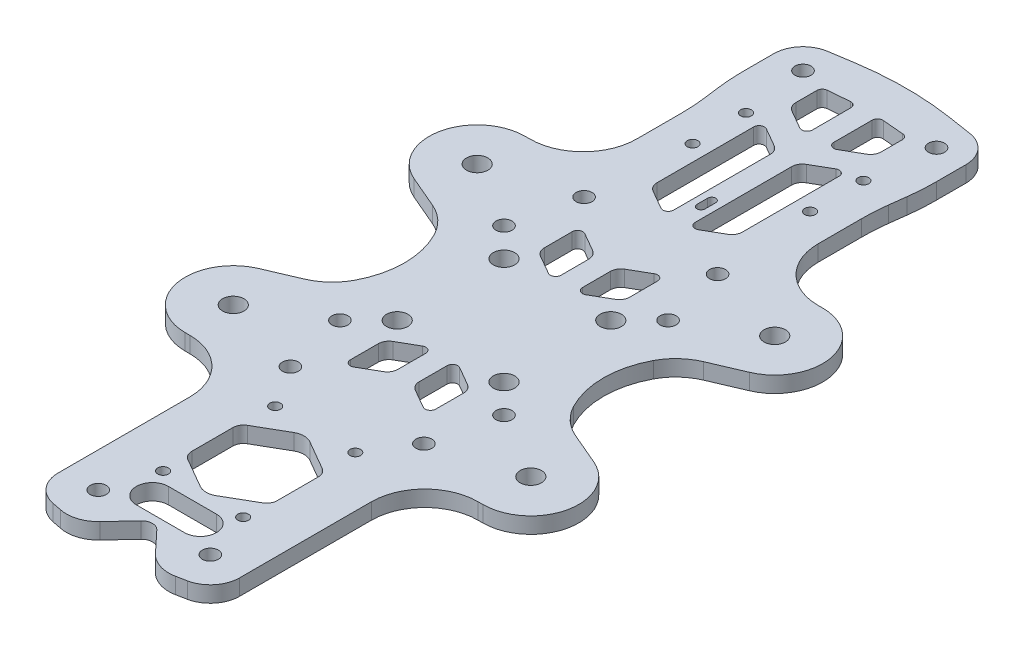
SolidWorks part; units mm, degrees
other "Markup1"
sketch "Sketch3" plane through (-36.8644, 3, -75.3176) normal (0, 1, 0) x (1, 0, 0)
material "Thornel Mat VMA"
ref_plane "Front Plane" through (0, 0, 0) normal (0, 0, 1) x (1, 0, 0)
ref_plane "Top Plane" through (0, 0, 0) normal (0, 1, 0) x (1, 0, 0)
ref_plane "Right Plane" through (0, 0, 0) normal (1, 0, 0) x (0, 0, -1)
sketch "Sketch1" plane through (0, 0, 0) normal (0, 1, 0) x (1, 0, 0)
  line L0 (7.0144, -13.8425) -> (3.5179, -11.8157)
  line L1 (-1.9927, -17.8721) -> (-1.9837, -12.6721)
  line L2 (-6.9856, 13.8181) -> (-3.4821, 11.8035)
  line L3 (2.0122, 17.9008) -> (2.0164, 12.6801)
  line L4 (2, 51.8812) -> (2, 33.7679)
  line L5 (-7, 34.9226) -> (-3.5, 32.9019)
  line L6 (3.5, 58.9019) -> (7, 60.9226)
  line L7 (-7, 60.9226) -> (-3.5, 58.9019)
  line L8 (-1.5, -37.866) -> (-7, -41.0415)
  line L9 (-6.6638, -69.1081) -> (-2.9181, -65.1127)
  line L10 (2.0164, -12.6801) -> (2.0122, -17.9008)
  line L11 (3, -19.6132) -> (6.5, -21.634)
  line L12 (8.002, -20.7686) -> (8.0113, -15.5764)
  line L13 (-3.4821, -11.8035) -> (-6.9856, -13.8181)
  line L14 (-7.9886, -15.5483) -> (-7.9977, -20.7675)
  line L15 (-6.5, -21.634) -> (-3, -19.6133)
  line L16 (-1.9837, 12.6721) -> (-1.9927, 17.8721)
  line L17 (-3, 19.6133) -> (-6.5, 21.634)
  line L18 (-7.9977, 20.7675) -> (-7.9886, 15.5483)
  line L19 (3.5179, 11.8157) -> (7.0144, 13.8425)
  line L20 (8.0113, 15.5764) -> (8.002, 20.7686)
  line L21 (6.5, 21.634) -> (3, 19.6132)
  line L22 (3.5, 32.9019) -> (7, 34.9226)
  line L23 (8, 36.6547) -> (8, 54.7679)
  line L24 (6.5, 55.634) -> (3, 53.6132)
  line L25 (-2, 33.7679) -> (-2, 51.8812)
  line L26 (-3, 53.6133) -> (-6.5, 55.634)
  line L27 (-8, 54.7679) -> (-8, 36.6546)
  line L28 (8, 62.6547) -> (8, 66.5946)
  line L29 (7.0872, 67.5908) -> (3.0872, 67.9408)
  line L30 (2, 66.9446) -> (2, 59.7679)
  line L31 (-2, 59.7679) -> (-2, 66.9446)
  line L32 (-3.0872, 67.9408) -> (-7.0872, 67.5908)
  line L33 (-8, 66.5946) -> (-8, 62.6547)
  line L34 (-8, -42.7735) -> (-8, -50.4641)
  line L35 (-7, -52.1962) -> (-1.5, -55.3716)
  line L36 (1.5, -55.3716) -> (7, -52.1962)
  line L37 (8, -50.4641) -> (8, -42.7735)
  line L38 (7, -41.0415) -> (1.5, -37.866)
  line L39 (-12.1839, -69.9325) -> (-10.3636, -70.2952)
  line L40 (-15, -41.84) -> (-15, -66.5)
  line L41 (-27.8644, -29.84) -> (-27, -29.84)
  line L42 (-24.6147, -13.8367) -> (-30.6171, -16.404)
  line L43 (-30.6171, 16.404) -> (-24.6147, 13.8367)
  line L44 (-26.9944, 29.84) -> (-27.8644, 29.84)
  line L45 (-14.9906, 49.9801) -> (-14.9944, 41.8344)
  line L46 (-15.6838, 58.0267) -> (-15.3029, 54.9969)
  line L47 (-16, 68.4976) -> (-15.9961, 62.9879)
  line L48 (-8.6637, 72.6434) -> (-13.0415, 71.9578)
  line L49 (13.0415, 71.9578) -> (8.6635, 72.6434)
  line L50 (15.9961, 62.9879) -> (15.9999, 68.4976)
  line L51 (15.3029, 54.9969) -> (15.6838, 58.0267)
  line L52 (14.9944, 41.8344) -> (14.9906, 49.98)
  line L53 (27.8644, 29.84) -> (26.9944, 29.84)
  line L54 (24.6147, 13.8367) -> (30.6171, 16.404)
  line L55 (30.6171, -16.404) -> (24.6147, -13.8367)
  line L56 (27, -29.84) -> (27.8644, -29.84)
  line L57 (15, -66.5) -> (15, -41.84)
  line L58 (10.3636, -70.2952) -> (12.1839, -69.9325)
  line L59 (2.9181, -65.1127) -> (6.6638, -69.1081)
  circle A0 centre (15.365, 15.365) radius 1.5
  circle A1 centre (15.365, -15.365) radius 1.5
  circle A2 centre (-15.365, -15.365) radius 1.5
  circle A3 centre (-15.365, 15.365) radius 1.5
  circle A4 centre (27.8644, -22.84) radius 2
  circle A5 centre (27.8644, 22.84) radius 2
  circle A6 centre (10.5, -65.5) radius 1.5
  circle A7 centre (-10, 10) radius 2
  circle A8 centre (-10, -10) radius 2
  circle A9 centre (-10.5, -65.5) radius 1.5
  circle A10 centre (-27.8644, -22.84) radius 2
  circle A11 centre (-27.8644, 22.84) radius 2
  circle A12 centre (12.5, 68.5) radius 1.5
  circle A13 centre (-12.5, 68.5) radius 1.5
  circle A14 centre (-10, -36.5) radius 1
  circle A15 centre (12.5, 27.5) radius 1.5
  circle A16 centre (-10, -56.5) radius 1
  circle A17 centre (-12.5, 27.5) radius 1.5
  circle A18 centre (12.5, -27.5) radius 1.5
  circle A19 centre (10, -36.5) radius 1
  circle A20 centre (-12.5, -27.5) radius 1.5
  circle A21 centre (10, -56.5) radius 1
  circle A22 centre (10, 10) radius 2
  circle A23 centre (10, -10) radius 2
  arc A24 (3.5179, -11.8157) -> (2.0164, -12.6801) centre (3.0164, -12.6808) ccw
  arc A25 (2.0122, -17.9008) -> (3, -19.6132) centre (3.9878, -17.9024) ccw
  arc A26 (6.5, -21.634) -> (8.002, -20.7686) centre (7.0007, -20.7668) ccw
  arc A27 (8.0113, -15.5764) -> (7.0144, -13.8425) centre (6.0113, -15.5728) ccw
  arc A28 (-1.9837, -12.6721) -> (-3.4821, -11.8035) centre (-2.9836, -12.6704) ccw
  arc A29 (-6.9856, -13.8181) -> (-7.9886, -15.5483) centre (-5.9887, -15.5518) ccw
  arc A30 (-7.9977, -20.7675) -> (-6.5, -21.634) centre (-6.9992, -20.7693) ccw
  arc A31 (-3, -19.6133) -> (-1.9927, -17.8721) centre (-4.0073, -17.8686) ccw
  arc A32 (-3.4821, 11.8035) -> (-1.9837, 12.6721) centre (-2.9836, 12.6704) ccw
  arc A33 (-1.9927, 17.8721) -> (-3, 19.6133) centre (-4.0073, 17.8686) ccw
  arc A34 (-6.5, 21.634) -> (-7.9977, 20.7675) centre (-6.9992, 20.7693) ccw
  arc A35 (-7.9886, 15.5483) -> (-6.9856, 13.8181) centre (-5.9887, 15.5518) ccw
  arc A36 (2.0164, 12.6801) -> (3.5179, 11.8157) centre (3.0164, 12.6808) ccw
  arc A37 (7.0144, 13.8425) -> (8.0113, 15.5764) centre (6.0113, 15.5728) ccw
  arc A38 (8.002, 20.7686) -> (6.5, 21.634) centre (7.0007, 20.7668) ccw
  arc A39 (3, 19.6132) -> (2.0122, 17.9008) centre (3.9878, 17.9024) ccw
  arc A40 (2, 33.7679) -> (3.5, 32.9019) centre (3, 33.7679) ccw
  arc A41 (7, 34.9226) -> (8, 36.6547) centre (6, 36.6547) ccw
  arc A42 (8, 54.7679) -> (6.5, 55.634) centre (7, 54.7679) ccw
  arc A43 (3, 53.6132) -> (2, 51.8812) centre (4, 51.8812) ccw
  arc A44 (-3.5, 32.9019) -> (-2, 33.7679) centre (-3, 33.7679) ccw
  arc A45 (-2, 51.8812) -> (-3, 53.6133) centre (-4, 51.8812) ccw
  arc A46 (-6.5, 55.634) -> (-8, 54.7679) centre (-7, 54.7679) ccw
  arc A47 (-8, 36.6546) -> (-7, 34.9226) centre (-6, 36.6546) ccw
  arc A48 (7, 60.9226) -> (8, 62.6547) centre (6, 62.6547) ccw
  arc A49 (8, 66.5946) -> (7.0872, 67.5908) centre (7, 66.5946) ccw
  arc A50 (3.0872, 67.9408) -> (2, 66.9446) centre (3, 66.9446) ccw
  arc A51 (2, 59.7679) -> (3.5, 58.9019) centre (3, 59.7679) ccw
  arc A52 (-3.5, 58.9019) -> (-2, 59.7679) centre (-3, 59.7679) ccw
  arc A53 (-2, 66.9446) -> (-3.0872, 67.9408) centre (-3, 66.9446) ccw
  arc A54 (-7.0872, 67.5908) -> (-8, 66.5946) centre (-7, 66.5946) ccw
  arc A55 (-8, 62.6547) -> (-7, 60.9226) centre (-6, 62.6547) ccw
  arc A56 (-7, -41.0415) -> (-8, -42.7735) centre (-6, -42.7735) ccw
  arc A57 (-8, -50.4641) -> (-7, -52.1962) centre (-6, -50.4641) ccw
  arc A58 (-1.5, -55.3716) -> (1.5, -55.3716) centre (0, -52.7735) ccw
  arc A59 (7, -52.1962) -> (8, -50.4641) centre (6, -50.4641) ccw
  arc A60 (8, -42.7735) -> (7, -41.0415) centre (6, -42.7735) ccw
  arc A61 (1.5, -37.866) -> (-1.5, -37.866) centre (0, -40.4641) ccw
  arc A62 (-10.3636, -70.2952) -> (-6.6638, -69.1081) centre (-9.582, -66.3723) ccw
  arc A63 (-15, -66.5) -> (-12.1839, -69.9325) centre (-11.5, -66.5) ccw
  arc A64 (-15, -41.84) -> (-27, -29.84) centre (-27, -41.84) ccw
  arc A65 (-30.6171, -16.404) -> (-27.8644, -29.84) centre (-27.8644, -22.84) ccw
  arc A66 (-24.6147, -13.8367) -> (-18.7242, -8.4106) centre (-29.3336, -2.8035) ccw
  arc A67 (-18.7242, -8.4106) -> (-18.7242, 8.4106) centre (-34.6384, 0) ccw
  arc A68 (-18.7242, 8.4106) -> (-24.6147, 13.8367) centre (-29.3336, 2.8035) ccw
  arc A69 (-27.8644, 29.84) -> (-30.6171, 16.404) centre (-27.8644, 22.84) ccw
  arc A70 (-26.9944, 29.84) -> (-14.9944, 41.8344) centre (-26.9944, 41.84) ccw
  arc A71 (-14.9906, 49.9801) -> (-15.3029, 54.9969) centre (-54.9906, 50.008) ccw
  arc A72 (-15.9961, 62.9879) -> (-15.6838, 58.0267) centre (24.0039, 63.0156) ccw
  arc A73 (-13.0415, 71.9578) -> (-16, 68.4976) centre (-12.5, 68.5) ccw
  arc A74 (8.6635, 72.6434) -> (-8.6637, 72.6434) centre (-0.0001, 17.3176) ccw
  arc A75 (15.9999, 68.4976) -> (13.0415, 71.9578) centre (12.5, 68.5) ccw
  arc A76 (15.6838, 58.0267) -> (15.9961, 62.9879) centre (-24.0039, 63.0156) ccw
  arc A77 (15.3029, 54.9969) -> (14.9906, 49.98) centre (54.9906, 50.008) ccw
  arc A78 (14.9944, 41.8344) -> (26.9944, 29.84) centre (26.9944, 41.84) ccw
  arc A79 (30.6171, 16.404) -> (27.8644, 29.84) centre (27.8644, 22.84) ccw
  arc A80 (24.6147, 13.8367) -> (18.7242, 8.4106) centre (29.3336, 2.8035) ccw
  arc A81 (18.7242, 8.4106) -> (18.7242, -8.4106) centre (34.6384, 0) ccw
  arc A82 (18.7242, -8.4106) -> (24.6147, -13.8367) centre (29.3336, -2.8035) ccw
  arc A83 (27.8644, -29.84) -> (30.6171, -16.404) centre (27.8644, -22.84) ccw
  arc A84 (27, -29.84) -> (15, -41.84) centre (27, -41.84) ccw
  arc A85 (12.1839, -69.9325) -> (15, -66.5) centre (11.5, -66.5) ccw
  arc A86 (6.6638, -69.1081) -> (10.3636, -70.2952) centre (9.582, -66.3723) ccw
  arc A87 (2.9181, -65.1127) -> (-2.9181, -65.1127) centre (0, -67.8485) ccw
sketch "Sketch2" plane through (0, 0, 0) normal (0, 1, 0) x (1, 0, 0)
  line L0 (-3.5, 32.9019) -> (3.5, 32.9019) construction
  line L5 (0, 38.9019) -> (0, 36.9019) construction
  line L7 (0.75, 38.9019) -> (0.75, 36.9019)
  line L8 (-0.75, 38.9019) -> (-0.75, 36.9019)
  line L9 (0, 0) -> (-0.0001, 75.3176) construction
  line L10 (0, 0) -> (0, -65.8485) construction
  line L11 (-18.6384, 0) -> (18.6384, 0) construction
  line L12 (-4.5, -61.3485) -> (4.5, -61.3485) construction
  line L13 (-4.5, -58.3485) -> (4.5, -58.3485)
  line L14 (-4.5, -64.3485) -> (4.5, -64.3485)
  line L15 (-14.0001, 51.3176) -> (13.9999, 51.3176) construction
  line L16 (-14.0001, 64.3176) -> (13.9999, 64.3176) construction
  line L17 (-14.0001, 64.3176) -> (-14.0001, 44.3176) construction
  line L18 (-14.0001, 44.3176) -> (13.9999, 44.3176) construction
  line L19 (13.9999, 64.3176) -> (13.9999, 44.3176) construction
  line L20 (-14.0001, 64.3176) -> (13.9999, 44.3176) construction
  line L21 (-14.0001, 44.3176) -> (13.9999, 64.3176) construction
  line L22 (-11.0001, 46.3176) -> (10.9999, 46.3176) construction
  line L513 (7, -41.0415) -> (1.5, -37.866) construction
  line L514 (-1.5, -37.866) -> (-7, -41.0415) construction
  line L515 (1.5, -55.3716) -> (7, -52.1962) construction
  line L516 (8, -50.4641) -> (8, -42.7735) construction
  line L517 (-8, -42.7735) -> (-8, -50.4641) construction
  line L518 (-7, -52.1962) -> (-1.5, -55.3716) construction
  line L519 (3, -19.6132) -> (6.5, -21.634) construction
  line L520 (7.0144, -13.8425) -> (3.5179, -11.8157) construction
  line L521 (8.002, -20.7686) -> (8.0113, -15.5764) construction
  line L522 (2.0164, -12.6801) -> (2.0122, -17.9008) construction
  line L523 (-6.5, -21.634) -> (-3, -19.6133) construction
  line L524 (-7.9886, -15.5483) -> (-7.9977, -20.7675) construction
  line L525 (-3.4821, -11.8035) -> (-6.9856, -13.8181) construction
  line L526 (-1.9927, -17.8721) -> (-1.9837, -12.6721) construction
  line L527 (3.5179, 11.8157) -> (7.0144, 13.8425) construction
  line L528 (8.0113, 15.5764) -> (8.002, 20.7686) construction
  line L529 (6.5, 21.634) -> (3, 19.6132) construction
  line L530 (-3, 19.6133) -> (-6.5, 21.634) construction
  line L531 (-7.9977, 20.7675) -> (-7.9886, 15.5483) construction
  line L532 (-1.9837, 12.6721) -> (-1.9927, 17.8721) construction
  line L533 (2.0122, 17.9008) -> (2.0164, 12.6801) construction
  line L534 (-6.9856, 13.8181) -> (-3.4821, 11.8035) construction
  line L535 (13.3509, 73.9337) -> (8.9729, 74.6193)
  line L536 (-8.9731, 74.6193) -> (-13.3509, 73.9338)
  line L537 (-18, 68.4962) -> (-17.9961, 62.9865)
  line L538 (-17.6682, 57.7773) -> (-17.2873, 54.7475)
  line L539 (17.9961, 62.9865) -> (17.9999, 68.4962)
  line L540 (17.2873, 54.7474) -> (17.6682, 57.7773)
  line L541 (-16.9906, 49.981) -> (-16.9944, 41.8353)
  line L542 (16.9944, 41.8353) -> (16.9906, 49.9814)
  line L543 (27.8644, 31.84) -> (26.9944, 31.84)
  line L544 (25.4012, 11.9979) -> (31.4036, 14.5651)
  line L545 (31.4036, -14.5651) -> (25.4012, -11.9979)
  line L546 (27, -31.84) -> (27.8644, -31.84)
  line L547 (17, -66.5) -> (17, -41.84)
  line L548 (10.7545, -72.2567) -> (12.5748, -71.894)
  line L549 (1.4591, -66.4806) -> (5.2048, -70.476)
  line L550 (-5.2048, -70.476) -> (-1.4591, -66.4806)
  line L551 (-12.5748, -71.894) -> (-10.7545, -72.2567)
  line L552 (-17, -41.84) -> (-17, -66.5)
  line L553 (-27.8644, -31.84) -> (-27, -31.84)
  line L554 (-25.4012, -11.9979) -> (-31.4036, -14.5651)
  line L555 (-31.4036, 14.5651) -> (-25.4012, 11.9979)
  line L556 (-26.9944, 31.84) -> (-27.8644, 31.84)
  line L557 (13.3509, 73.9337) -> (8.9729, 74.6193)
  line L558 (-8.9731, 74.6193) -> (-13.3509, 73.9338)
  line L559 (-18, 68.4962) -> (-17.9961, 62.9865)
  line L560 (-17.6682, 57.7773) -> (-17.2873, 54.7475)
  line L561 (17.9961, 62.9865) -> (17.9999, 68.4962)
  line L562 (17.2873, 54.7474) -> (17.6682, 57.7773)
  line L563 (-16.9906, 49.981) -> (-16.9944, 41.8353)
  line L564 (16.9944, 41.8353) -> (16.9906, 49.9814)
  line L565 (27.8644, 31.84) -> (26.9944, 31.84)
  line L566 (25.4012, 11.9979) -> (31.4036, 14.5651)
  line L567 (31.4036, -14.5651) -> (25.4012, -11.9979)
  line L568 (27, -31.84) -> (27.8644, -31.84)
  line L569 (17, -66.5) -> (17, -41.84)
  line L570 (10.7545, -72.2567) -> (12.5748, -71.894)
  line L571 (1.4591, -66.4806) -> (5.2048, -70.476)
  line L572 (-5.2048, -70.476) -> (-1.4591, -66.4806)
  line L573 (-12.5748, -71.894) -> (-10.7545, -72.2567)
  line L574 (-17, -41.84) -> (-17, -66.5)
  line L575 (-27.8644, -31.84) -> (-27, -31.84)
  line L576 (-25.4012, -11.9979) -> (-31.4036, -14.5651)
  line L577 (-31.4036, 14.5651) -> (-25.4012, 11.9979)
  line L578 (-26.9944, 31.84) -> (-27.8644, 31.84)
  line L579 (3.5, 32.9019) -> (7, 34.9226) construction
  line L580 (-7, 34.9226) -> (-3.5, 32.9019) construction
  line L581 (8, 36.6547) -> (8, 54.7679) construction
  line L582 (6.5, 55.634) -> (3, 53.6132) construction
  line L583 (-3, 53.6133) -> (-6.5, 55.634) construction
  line L584 (-2, 33.7679) -> (-2, 51.8812) construction
  line L585 (2, 51.8812) -> (2, 33.7679) construction
  line L586 (-8, 54.7679) -> (-8, 36.6546) construction
  line L587 (3.5, 58.9019) -> (7, 60.9226) construction
  line L588 (8, 62.6547) -> (8, 66.5946) construction
  line L589 (7.0872, 67.5908) -> (3.0872, 67.9408) construction
  line L590 (2, 66.9446) -> (2, 59.7679) construction
  line L591 (-7, 60.9226) -> (-3.5, 58.9019) construction
  line L592 (-2, 59.7679) -> (-2, 66.9446) construction
  line L593 (-3.0872, 67.9408) -> (-7.0872, 67.5908) construction
  line L594 (-8, 66.5946) -> (-8, 62.6547) construction
  line L595 (7, -41.0415) -> (1.5, -37.866)
  line L596 (-1.5, -37.866) -> (-7, -41.0415)
  line L597 (1.5, -55.3716) -> (7, -52.1962)
  line L598 (8, -50.4641) -> (8, -42.7735)
  line L599 (-8, -42.7735) -> (-8, -50.4641)
  line L600 (-7, -52.1962) -> (-1.5, -55.3716)
  line L601 (3, -19.6132) -> (6.5, -21.634)
  line L602 (7.0144, -13.8425) -> (3.5179, -11.8157)
  line L603 (8.002, -20.7686) -> (8.0113, -15.5764)
  line L604 (2.0164, -12.6801) -> (2.0122, -17.9008)
  line L605 (-6.5, -21.634) -> (-3, -19.6133)
  line L606 (-7.9886, -15.5483) -> (-7.9977, -20.7675)
  line L607 (-3.4821, -11.8035) -> (-6.9856, -13.8181)
  line L608 (-1.9927, -17.8721) -> (-1.9837, -12.6721)
  line L609 (3.5179, 11.8157) -> (7.0144, 13.8425)
  line L610 (8.0113, 15.5764) -> (8.002, 20.7686)
  line L611 (6.5, 21.634) -> (3, 19.6132)
  line L612 (-3, 19.6133) -> (-6.5, 21.634)
  line L613 (-7.9977, 20.7675) -> (-7.9886, 15.5483)
  line L614 (-1.9837, 12.6721) -> (-1.9927, 17.8721)
  line L615 (2.0122, 17.9008) -> (2.0164, 12.6801)
  line L616 (-6.9856, 13.8181) -> (-3.4821, 11.8035)
  line L617 (3.5, 32.9019) -> (7, 34.9226)
  line L618 (-7, 34.9226) -> (-3.5, 32.9019)
  line L619 (8, 36.6547) -> (8, 54.7679)
  line L620 (6.5, 55.634) -> (3, 53.6132)
  line L621 (-3, 53.6133) -> (-6.5, 55.634)
  line L622 (-2, 33.7679) -> (-2, 51.8812)
  line L623 (2, 51.8812) -> (2, 33.7679)
  line L624 (-8, 54.7679) -> (-8, 36.6546)
  line L625 (3.5, 58.9019) -> (7, 60.9226)
  line L626 (8, 62.6547) -> (8, 66.5946)
  line L627 (7.0872, 67.5908) -> (3.0872, 67.9408)
  line L628 (2, 66.9446) -> (2, 59.7679)
  line L629 (-7, 60.9226) -> (-3.5, 58.9019)
  line L630 (-2, 59.7679) -> (-2, 66.9446)
  line L631 (-3.0872, 67.9408) -> (-7.0872, 67.5908)
  line L632 (-8, 66.5946) -> (-8, 62.6547)
  arc A1 (0.75, 38.9019) -> (-0.75, 38.9019) centre (0, 38.9019) ccw
  arc A2 (-0.75, 36.9019) -> (0.75, 36.9019) centre (0, 36.9019) ccw
  circle A3 centre (-12.5, 68.5) radius 2.75 construction
  circle A4 centre (12.4998, 68.5) radius 2.75 construction
  circle A5 centre (-7.5, -35.3485) radius 1
  circle A6 centre (-7.5, -56.3485) radius 1
  circle A7 centre (7.5, -35.3485) radius 1
  circle A8 centre (7.5, -56.3485) radius 1
  arc A9 (-4.5, -58.3485) -> (-4.5, -64.3485) centre (-4.5, -61.3485) ccw
  arc A10 (4.5, -64.3485) -> (4.5, -58.3485) centre (4.5, -61.3485) ccw
  circle A11 centre (-10.5, -65.5) radius 2.75 construction
  circle A12 centre (10.5, -65.5) radius 2.75 construction
  circle A16 centre (-11.0001, 46.3176) radius 1
  circle A17 centre (10.9999, 46.3176) radius 1
  circle A18 centre (10.9999, 56.3176) radius 1
  circle A19 centre (-11.0001, 56.3176) radius 1
  arc A666 (8, -42.7735) -> (7, -41.0415) centre (6, -42.7735) ccw construction
  arc A667 (1.5, -37.866) -> (-1.5, -37.866) centre (0, -40.4641) ccw construction
  arc A668 (-7, -41.0415) -> (-8, -42.7735) centre (-6, -42.7735) ccw construction
  arc A669 (-8, -50.4641) -> (-7, -52.1962) centre (-6, -50.4641) ccw construction
  arc A670 (-1.5, -55.3716) -> (1.5, -55.3716) centre (0, -52.7735) ccw construction
  arc A671 (7, -52.1962) -> (8, -50.4641) centre (6, -50.4641) ccw construction
  circle A674 centre (10.5, -65.5) radius 1.5 construction
  circle A675 centre (-10.5, -65.5) radius 1.5 construction
  arc A676 (6.5, -21.634) -> (8.002, -20.7686) centre (7.0007, -20.7668) ccw construction
  arc A677 (2.0122, -17.9008) -> (3, -19.6132) centre (3.9878, -17.9024) ccw construction
  arc A678 (3.5179, -11.8157) -> (2.0164, -12.6801) centre (3.0164, -12.6808) ccw construction
  arc A679 (8.0113, -15.5764) -> (7.0144, -13.8425) centre (6.0113, -15.5728) ccw construction
  arc A680 (-3, -19.6133) -> (-1.9927, -17.8721) centre (-4.0073, -17.8686) ccw construction
  arc A681 (-7.9977, -20.7675) -> (-6.5, -21.634) centre (-6.9992, -20.7693) ccw construction
  arc A682 (-6.9856, -13.8181) -> (-7.9886, -15.5483) centre (-5.9887, -15.5518) ccw construction
  arc A683 (-1.9837, -12.6721) -> (-3.4821, -11.8035) centre (-2.9836, -12.6704) ccw construction
  circle A684 centre (10, -10) radius 2 construction
  circle A685 centre (15.365, -15.365) radius 1.5 construction
  circle A686 centre (27.8644, -22.84) radius 2 construction
  circle A687 centre (12.5, -27.5) radius 1.5 construction
  circle A690 centre (-10, -10) radius 2 construction
  circle A691 centre (-15.365, -15.365) radius 1.5 construction
  arc A692 (8.9729, 74.6193) -> (-8.9731, 74.6193) centre (-0.0001, 17.3176) ccw
  arc A693 (-13.3509, 73.9338) -> (-18, 68.4962) centre (-12.5, 68.5) ccw
  arc A694 (-17.9961, 62.9865) -> (-17.6682, 57.7773) centre (24.0039, 63.0156) ccw
  arc A695 (17.9999, 68.4962) -> (13.3509, 73.9337) centre (12.5, 68.5) ccw
  arc A696 (17.6682, 57.7773) -> (17.9961, 62.9865) centre (-24.0039, 63.0156) ccw
  arc A697 (-16.9906, 49.981) -> (-17.2873, 54.7475) centre (-54.9906, 50.008) ccw
  arc A698 (17.2873, 54.7474) -> (16.9906, 49.9814) centre (54.9906, 50.008) ccw
  arc A699 (16.9944, 41.8353) -> (26.9944, 31.84) centre (26.9944, 41.84) ccw
  arc A700 (31.4036, 14.5651) -> (27.8644, 31.84) centre (27.8644, 22.84) ccw
  arc A701 (25.4012, 11.9979) -> (20.4924, 7.4761) centre (29.3336, 2.8035) ccw
  arc A702 (20.4924, 7.4761) -> (20.4924, -7.4761) centre (34.6384, 0) ccw
  arc A703 (20.4924, -7.4761) -> (25.4012, -11.9979) centre (29.3336, -2.8035) ccw
  arc A704 (27.8644, -31.84) -> (31.4036, -14.5651) centre (27.8644, -22.84) ccw
  arc A705 (27, -31.84) -> (17, -41.84) centre (27, -41.84) ccw
  arc A706 (12.5748, -71.894) -> (17, -66.5) centre (11.5, -66.5) ccw
  arc A707 (5.2048, -70.476) -> (10.7545, -72.2567) centre (9.582, -66.3723) ccw
  arc A708 (1.4591, -66.4806) -> (-1.4591, -66.4806) centre (0, -67.8485) ccw
  arc A709 (-10.7545, -72.2567) -> (-5.2048, -70.476) centre (-9.582, -66.3723) ccw
  arc A710 (-17, -66.5) -> (-12.5748, -71.894) centre (-11.5, -66.5) ccw
  arc A711 (-17, -41.84) -> (-27, -31.84) centre (-27, -41.84) ccw
  arc A712 (-31.4036, -14.5651) -> (-27.8644, -31.84) centre (-27.8644, -22.84) ccw
  arc A713 (-25.4012, -11.9979) -> (-20.4924, -7.4761) centre (-29.3336, -2.8035) ccw
  arc A714 (-20.4924, -7.4761) -> (-20.4924, 7.4761) centre (-34.6384, 0) ccw
  arc A715 (-20.4924, 7.4761) -> (-25.4012, 11.9979) centre (-29.3336, 2.8035) ccw
  arc A716 (-27.8644, 31.84) -> (-31.4036, 14.5651) centre (-27.8644, 22.84) ccw
  arc A717 (-26.9944, 31.84) -> (-16.9944, 41.8353) centre (-26.9944, 41.84) ccw
  arc A718 (8.9729, 74.6193) -> (-8.9731, 74.6193) centre (-0.0001, 17.3176) ccw
  arc A719 (-13.3509, 73.9338) -> (-18, 68.4962) centre (-12.5, 68.5) ccw
  arc A720 (-17.9961, 62.9865) -> (-17.6682, 57.7773) centre (24.0039, 63.0156) ccw
  arc A721 (17.9999, 68.4962) -> (13.3509, 73.9337) centre (12.5, 68.5) ccw
  arc A722 (17.6682, 57.7773) -> (17.9961, 62.9865) centre (-24.0039, 63.0156) ccw
  arc A723 (-16.9906, 49.981) -> (-17.2873, 54.7475) centre (-54.9906, 50.008) ccw
  arc A724 (17.2873, 54.7474) -> (16.9906, 49.9814) centre (54.9906, 50.008) ccw
  arc A725 (16.9944, 41.8353) -> (26.9944, 31.84) centre (26.9944, 41.84) ccw
  arc A726 (31.4036, 14.5651) -> (27.8644, 31.84) centre (27.8644, 22.84) ccw
  arc A727 (25.4012, 11.9979) -> (20.4924, 7.4761) centre (29.3336, 2.8035) ccw
  arc A728 (20.4924, 7.4761) -> (20.4924, -7.4761) centre (34.6384, 0) ccw
  arc A729 (20.4924, -7.4761) -> (25.4012, -11.9979) centre (29.3336, -2.8035) ccw
  arc A730 (27.8644, -31.84) -> (31.4036, -14.5651) centre (27.8644, -22.84) ccw
  arc A731 (27, -31.84) -> (17, -41.84) centre (27, -41.84) ccw
  arc A732 (12.5748, -71.894) -> (17, -66.5) centre (11.5, -66.5) ccw
  arc A733 (5.2048, -70.476) -> (10.7545, -72.2567) centre (9.582, -66.3723) ccw
  arc A734 (1.4591, -66.4806) -> (-1.4591, -66.4806) centre (0, -67.8485) ccw
  arc A735 (-10.7545, -72.2567) -> (-5.2048, -70.476) centre (-9.582, -66.3723) ccw
  arc A736 (-17, -66.5) -> (-12.5748, -71.894) centre (-11.5, -66.5) ccw
  arc A737 (-17, -41.84) -> (-27, -31.84) centre (-27, -41.84) ccw
  arc A738 (-31.4036, -14.5651) -> (-27.8644, -31.84) centre (-27.8644, -22.84) ccw
  arc A739 (-25.4012, -11.9979) -> (-20.4924, -7.4761) centre (-29.3336, -2.8035) ccw
  arc A740 (-20.4924, -7.4761) -> (-20.4924, 7.4761) centre (-34.6384, 0) ccw
  arc A741 (-20.4924, 7.4761) -> (-25.4012, 11.9979) centre (-29.3336, 2.8035) ccw
  arc A742 (-27.8644, 31.84) -> (-31.4036, 14.5651) centre (-27.8644, 22.84) ccw
  arc A743 (-26.9944, 31.84) -> (-16.9944, 41.8353) centre (-26.9944, 41.84) ccw
  circle A744 centre (-12.5, -27.5) radius 1.5 construction
  circle A745 centre (-27.8644, -22.84) radius 2 construction
  circle A746 centre (27.8644, 22.84) radius 2 construction
  circle A747 centre (15.365, 15.365) radius 1.5 construction
  circle A748 centre (10, 10) radius 2 construction
  arc A749 (2.0164, 12.6801) -> (3.5179, 11.8157) centre (3.0164, 12.6808) ccw construction
  arc A750 (7.0144, 13.8425) -> (8.0113, 15.5764) centre (6.0113, 15.5728) ccw construction
  arc A751 (8.002, 20.7686) -> (6.5, 21.634) centre (7.0007, 20.7668) ccw construction
  arc A752 (3, 19.6132) -> (2.0122, 17.9008) centre (3.9878, 17.9024) ccw construction
  arc A753 (-1.9927, 17.8721) -> (-3, 19.6133) centre (-4.0073, 17.8686) ccw construction
  arc A754 (-6.5, 21.634) -> (-7.9977, 20.7675) centre (-6.9992, 20.7693) ccw construction
  arc A755 (-7.9886, 15.5483) -> (-6.9856, 13.8181) centre (-5.9887, 15.5518) ccw construction
  arc A756 (-3.4821, 11.8035) -> (-1.9837, 12.6721) centre (-2.9836, 12.6704) ccw construction
  circle A757 centre (-10, 10) radius 2 construction
  circle A758 centre (-15.365, 15.365) radius 1.5 construction
  circle A759 centre (-27.8644, 22.84) radius 2 construction
  circle A760 centre (-12.5, 27.5) radius 1.5 construction
  circle A761 centre (12.5, 27.5) radius 1.5 construction
  arc A762 (7, 34.9226) -> (8, 36.6547) centre (6, 36.6547) ccw construction
  arc A763 (2, 33.7679) -> (3.5, 32.9019) centre (3, 33.7679) ccw construction
  arc A764 (-8, 36.6546) -> (-7, 34.9226) centre (-6, 36.6546) ccw construction
  arc A765 (-3.5, 32.9019) -> (-2, 33.7679) centre (-3, 33.7679) ccw construction
  arc A766 (8, 54.7679) -> (6.5, 55.634) centre (7, 54.7679) ccw construction
  arc A767 (3, 53.6132) -> (2, 51.8812) centre (4, 51.8812) ccw construction
  arc A768 (-2, 51.8812) -> (-3, 53.6133) centre (-4, 51.8812) ccw construction
  arc A769 (-6.5, 55.634) -> (-8, 54.7679) centre (-7, 54.7679) ccw construction
  arc A770 (2, 59.7679) -> (3.5, 58.9019) centre (3, 59.7679) ccw construction
  arc A771 (7, 60.9226) -> (8, 62.6547) centre (6, 62.6547) ccw construction
  arc A772 (8, 66.5946) -> (7.0872, 67.5908) centre (7, 66.5946) ccw construction
  arc A773 (3.0872, 67.9408) -> (2, 66.9446) centre (3, 66.9446) ccw construction
  arc A774 (-8, 62.6547) -> (-7, 60.9226) centre (-6, 62.6547) ccw construction
  arc A775 (-3.5, 58.9019) -> (-2, 59.7679) centre (-3, 59.7679) ccw construction
  arc A776 (-2, 66.9446) -> (-3.0872, 67.9408) centre (-3, 66.9446) ccw construction
  arc A777 (-7.0872, 67.5908) -> (-8, 66.5946) centre (-7, 66.5946) ccw construction
  circle A778 centre (-12.5, 68.5) radius 1.5 construction
  circle A779 centre (12.5, 68.5) radius 1.5 construction
  arc A780 (8, -42.7735) -> (7, -41.0415) centre (6, -42.7735) ccw
  arc A781 (1.5, -37.866) -> (-1.5, -37.866) centre (0, -40.4641) ccw
  arc A782 (-7, -41.0415) -> (-8, -42.7735) centre (-6, -42.7735) ccw
  arc A783 (-8, -50.4641) -> (-7, -52.1962) centre (-6, -50.4641) ccw
  arc A784 (-1.5, -55.3716) -> (1.5, -55.3716) centre (0, -52.7735) ccw
  arc A785 (7, -52.1962) -> (8, -50.4641) centre (6, -50.4641) ccw
  circle A788 centre (10.5, -65.5) radius 1.5
  circle A789 centre (-10.5, -65.5) radius 1.5
  arc A790 (6.5, -21.634) -> (8.002, -20.7686) centre (7.0007, -20.7668) ccw
  arc A791 (2.0122, -17.9008) -> (3, -19.6132) centre (3.9878, -17.9024) ccw
  arc A792 (3.5179, -11.8157) -> (2.0164, -12.6801) centre (3.0164, -12.6808) ccw
  arc A793 (8.0113, -15.5764) -> (7.0144, -13.8425) centre (6.0113, -15.5728) ccw
  arc A794 (-3, -19.6133) -> (-1.9927, -17.8721) centre (-4.0073, -17.8686) ccw
  arc A795 (-7.9977, -20.7675) -> (-6.5, -21.634) centre (-6.9992, -20.7693) ccw
  arc A796 (-6.9856, -13.8181) -> (-7.9886, -15.5483) centre (-5.9887, -15.5518) ccw
  arc A797 (-1.9837, -12.6721) -> (-3.4821, -11.8035) centre (-2.9836, -12.6704) ccw
  circle A798 centre (10, -10) radius 2
  circle A799 centre (15.365, -15.365) radius 1.5
  circle A800 centre (27.8644, -22.84) radius 2
  circle A801 centre (12.5, -27.5) radius 1.5
  circle A804 centre (-10, -10) radius 2
  circle A805 centre (-15.365, -15.365) radius 1.5
  circle A806 centre (-12.5, -27.5) radius 1.5
  circle A807 centre (-27.8644, -22.84) radius 2
  circle A808 centre (27.8644, 22.84) radius 2
  circle A809 centre (15.365, 15.365) radius 1.5
  circle A810 centre (10, 10) radius 2
  arc A811 (2.0164, 12.6801) -> (3.5179, 11.8157) centre (3.0164, 12.6808) ccw
  arc A812 (7.0144, 13.8425) -> (8.0113, 15.5764) centre (6.0113, 15.5728) ccw
  arc A813 (8.002, 20.7686) -> (6.5, 21.634) centre (7.0007, 20.7668) ccw
  arc A814 (3, 19.6132) -> (2.0122, 17.9008) centre (3.9878, 17.9024) ccw
  arc A815 (-1.9927, 17.8721) -> (-3, 19.6133) centre (-4.0073, 17.8686) ccw
  arc A816 (-6.5, 21.634) -> (-7.9977, 20.7675) centre (-6.9992, 20.7693) ccw
  arc A817 (-7.9886, 15.5483) -> (-6.9856, 13.8181) centre (-5.9887, 15.5518) ccw
  arc A818 (-3.4821, 11.8035) -> (-1.9837, 12.6721) centre (-2.9836, 12.6704) ccw
  circle A819 centre (-10, 10) radius 2
  circle A820 centre (-15.365, 15.365) radius 1.5
  circle A821 centre (-27.8644, 22.84) radius 2
  circle A822 centre (-12.5, 27.5) radius 1.5
  circle A823 centre (12.5, 27.5) radius 1.5
  arc A824 (7, 34.9226) -> (8, 36.6547) centre (6, 36.6547) ccw
  arc A825 (2, 33.7679) -> (3.5, 32.9019) centre (3, 33.7679) ccw
  arc A826 (-8, 36.6546) -> (-7, 34.9226) centre (-6, 36.6546) ccw
  arc A827 (-3.5, 32.9019) -> (-2, 33.7679) centre (-3, 33.7679) ccw
  arc A828 (8, 54.7679) -> (6.5, 55.634) centre (7, 54.7679) ccw
  arc A829 (3, 53.6132) -> (2, 51.8812) centre (4, 51.8812) ccw
  arc A830 (-2, 51.8812) -> (-3, 53.6133) centre (-4, 51.8812) ccw
  arc A831 (-6.5, 55.634) -> (-8, 54.7679) centre (-7, 54.7679) ccw
  arc A832 (2, 59.7679) -> (3.5, 58.9019) centre (3, 59.7679) ccw
  arc A833 (7, 60.9226) -> (8, 62.6547) centre (6, 62.6547) ccw
  arc A834 (8, 66.5946) -> (7.0872, 67.5908) centre (7, 66.5946) ccw
  arc A835 (3.0872, 67.9408) -> (2, 66.9446) centre (3, 66.9446) ccw
  arc A836 (-8, 62.6547) -> (-7, 60.9226) centre (-6, 62.6547) ccw
  arc A837 (-3.5, 58.9019) -> (-2, 59.7679) centre (-3, 59.7679) ccw
  arc A838 (-2, 66.9446) -> (-3.0872, 67.9408) centre (-3, 66.9446) ccw
  arc A839 (-7.0872, 67.5908) -> (-8, 66.5946) centre (-7, 66.5946) ccw
  circle A840 centre (-12.5, 68.5) radius 1.5
  circle A841 centre (12.5, 68.5) radius 1.5
  point P26 (0, 37.9019)
  point P33 (0.75, 37.9019)
  point P72 (0, 0)
  point P75 (0, 32.9019)
  point P138 (0, -61.3485)
  point P165 (-0.0001, 54.3176)
  point P190 (-0.0001, 46.3176)
  dimension "D2" = 1.5
  dimension "D10" = 20
  dimension "D15" = 11
  dimension "D14" = 28
  dimension "D16" = 2
  dimension "D17" = 2
  dimension "D18" = 2
  dimension "D3" = 2
  dimension "D4" = 5
  dimension "12.5" = 9
  dimension "D11" = 6
  dimension "D12" = 1.5
  dimension "D19" = 22
  dimension "D20" = 7
  dimension "D1" = 2
extrude "Boss-Extrude1" add sketch "Sketch2" along normal blind 3
